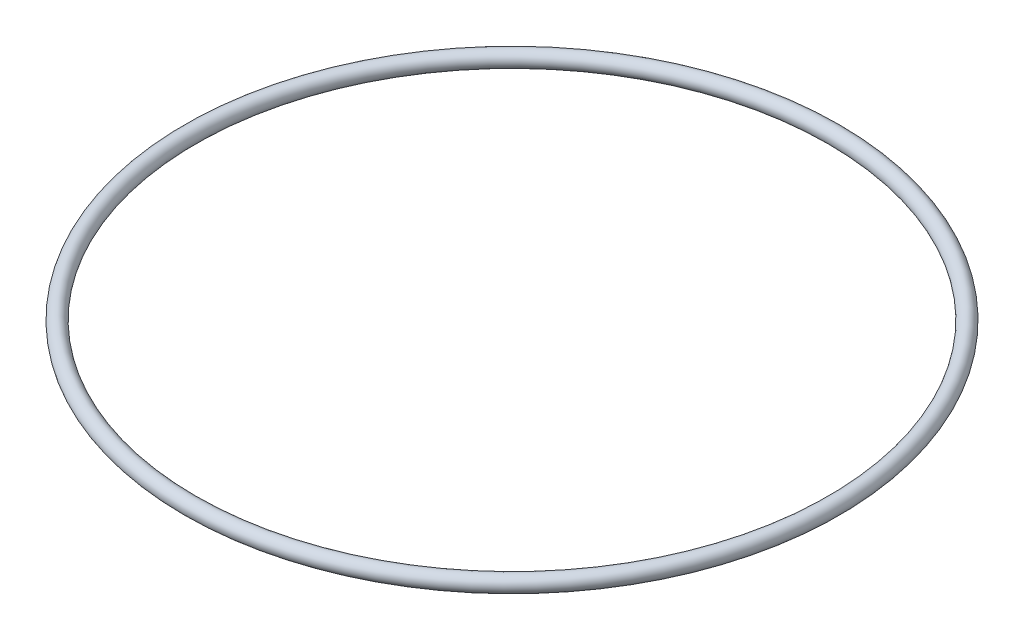
SolidWorks part; units mm, degrees
material "Rubber"
ref_plane "Front Plane" through (0, 0, 0) normal (0, 0, 1) x (1, 0, 0)
ref_plane "Top Plane" through (0, 0, 0) normal (0, 1, 0) x (1, 0, 0)
ref_plane "Right Plane" through (0, 0, 0) normal (1, 0, 0) x (0, 0, -1)
sketch "Sketch1" plane through (0, 0, 0) normal (0, 0, 1) x (1, 0, 0)
  line L0 (0, 0) -> (0, 11.8797) construction
  circle A0 centre (-61.5, 0) radius 1.5
  dimension "D1" = 63
  dimension "D2" = 60
revolve "Revolve1" add sketch "Sketch1" angle 360 about L0
